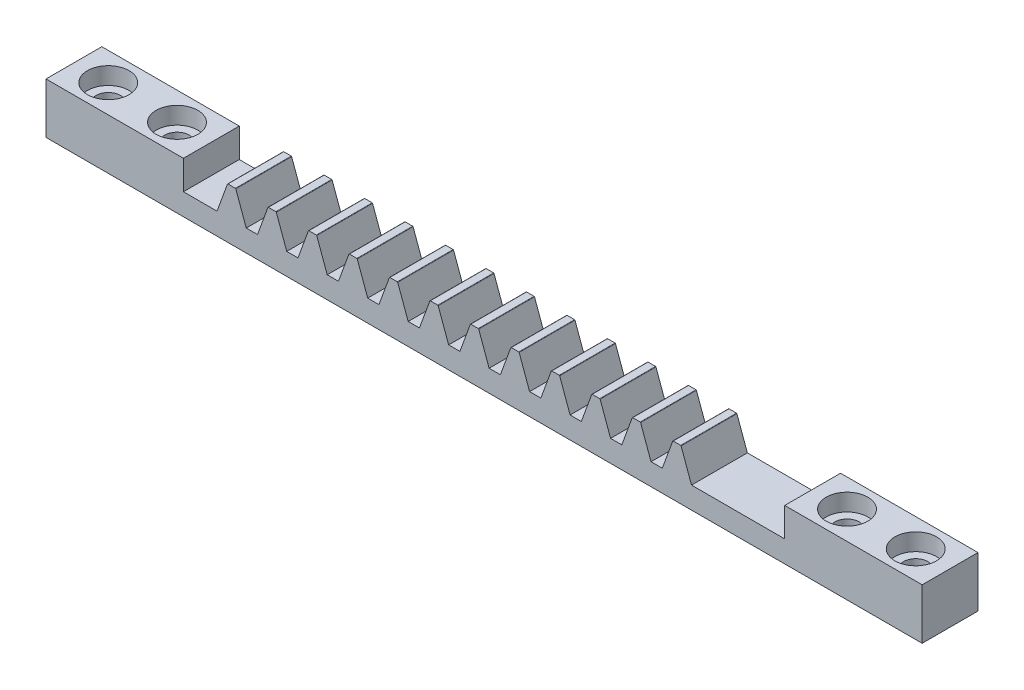
SolidWorks part; units mm, degrees
extrude "Blank" add sketch "BlankSke" against normal blind 6.5
sketch "BlankSke" plane through (0, 0, 0) normal (0, 0, 1) x (1, 0, 0)
  line L1 (0, 0) -> (56.5, 0)
  line L2 (0, 0) -> (0, 6)
  line L3 (0, 6) -> (56.5, 6)
  line L4 (56.5, 0) -> (56.5, 6)
  dimension "Length" = 56.5
  dimension "Blank_height" = 6
ref_plane "Plane1" through (0, 0, 0) normal (0, 0, 1) x (1, 0, 0)
ref_plane "Plane2" through (0, 0, 0) normal (0, 1, 0) x (1, 0, 0)
ref_plane "Plane3" through (0, 0, 0) normal (1, 0, 0) x (0, 0, -1)
sketch "HoldingSke" plane through (0, 0, 0) normal (0, 1, 0) x (1, 0, 0)
  line L0 (0, 0) -> (0.0928, 0.6602)
  line L1 (-15, 0) -> (100, 0) construction
  line L2 (0, 0) -> (-2.1039, 2.3779)
  line L3 (0, 0) -> (-11.863, 4.5341)
  line L4 (0, 0) -> (8.4147, 1.9427)
  line L5 (0, 0) -> (-23.7986, -8.8762)
  line L6 (0, 0) -> (-10.5278, -7.1032)
  line L9 (-71.009, 38.7566) -> (-17.9163, 58.0807)
  line L10 (-76.2, 3.8779) -> (-71.7, 3.8779)
  line L11 (0, 0) -> (-6.5, 0)
  line L12 (-76.2, 101.6) -> (-76.147, 101.6)
  line L13 (24.9733, 27.94) -> (52.9518, 28.4284)
  line L14 (24.9733, 27.94) -> (24.9743, 27.94)
  line L15 (24.9733, 27.94) -> (100.4006, 29.5858)
  circle A0 centre (0, 0) radius 19.05
  circle A1 centre (0, 0) radius 2.25
  circle A2 centre (0, 0) radius 12.7
  dimension "MPH" = 4.5
  dimension "Diameter" = 38.1
  dimension "Num_teeth" = 13
  dimension "Pitch" = 0.6667
  dimension "Show_teeth" = 998
  dimension "Thickness" = 12.7
  dimension "Ap" = 20
  dimension "Pitch_height" = 4.5
  dimension "Width" = 6.5
  dimension "Backlash" = 0.053
  dimension "Addendum_fac" = 1
  dimension "Dedendum_fac" = 1.25
  dimension "Clearance_fac" = 0.25
  dimension "Dedendum_add" = 0.001
  dimension "Length" = 56.5
  dimension "Module" = 1.5
sketch "TooCutSkeIll" plane through (0, 0, 0) normal (0, 0, 1) x (1, 0, 0)
  line L0 (-1.8687, 5.9605) -> (-0.7447, 2.8724)
  line L1 (-0.3914, 2.625) -> (0.3914, 2.625)
  line L2 (0.7447, 2.8724) -> (1.8687, 5.9605)
  line L3 (56.5, 6) -> (0, 6) construction
  line L4 (0, 0) -> (0, 64.897) construction
  line L5 (-13.208, 4.5) -> (12.954, 4.5) construction
  line L6 (0, 0) -> (56.5, 0) construction
  line L7 (1.3371, 4.5) -> (1.3371, 48.7463) construction
  line L8 (-1.3371, 4.5) -> (-1.3371, 48.7463) construction
  line L9 (1.9251, 6) -> (1.9251, 6.0254)
  line L10 (-1.9251, 6) -> (-1.9251, 6.0254)
  line L11 (-1.9251, 6.0254) -> (1.9251, 6.0254)
  arc A0 (0.3914, 2.625) -> (0.7447, 2.8724) centre (0.3914, 3.001) ccw
  arc A1 (-0.7447, 2.8724) -> (-0.3914, 2.625) centre (-0.3914, 3.001) ccw
  arc A2 (1.9251, 6) -> (1.8687, 5.9605) centre (1.9251, 5.94) ccw
  arc A3 (-1.8687, 5.9605) -> (-1.9251, 6) centre (-1.9251, 5.94) ccw
  dimension "Pitch_height" = 4.5
  dimension "Addendum_plus" = 1.5254
  dimension "Pressure_angle" = 20
  dimension "Gap_width" = 2.6742
  dimension "Dedendum" = 1.875
extrude "ToothCutIll" cut sketch "TooCutSkeIll" against normal through all
sketch "TooCutSkeSim" plane through (0, 0, 0) normal (0, 0, 1) x (1, 0, 0)
  line L0 (0.6547, 2.625) -> (-0.6547, 2.625)
  line L1 (1.8923, 6.0254) -> (0.6547, 2.625)
  line L2 (0, 17.4625) -> (0, 53.467) construction
  line L3 (1.8923, 6.0254) -> (-1.8923, 6.0254)
  line L6 (-1.8923, 6.0254) -> (-0.6547, 2.625)
  line L9 (-1.3371, 4.5) -> (1.3371, 4.5) construction
  line L10 (0, 0) -> (56.5, 0) construction
  line L11 (1.3371, 4.5) -> (1.3371, 53.467) construction
  line L12 (-1.3371, 4.5) -> (-1.3371, 53.467) construction
  dimension "Pitch_height" = 4.5
  dimension "Addendum_plus" = 1.5254
  dimension "Pressure_angle" = 20
  dimension "Gap_width" = 2.6742
  dimension "Dedendum" = 1.875
extrude "ToothCutSim" cut sketch "TooCutSkeSim" against normal through all
pattern_linear "TeethCuts" count 13 spacing 4.7124 along (1, 0, 0) of "ToothCutIll", "ToothCutSim"
ref_plane "基准面1" through (0, 0, 0) normal (0, -1, 0) x (-1, 0, 0)
sketch "草图4" plane through (0, 0, 0) normal (0, -1, 0) x (-1, 0, 0)
  line L0 (0, 0) -> (19.255, 0)
  line L1 (19.255, 0) -> (19.255, 6.5)
  line L2 (19.255, 6.5) -> (0, 6.5)
  line L3 (0, 6.5) -> (0, 0)
  line L4 (-56.5, 0) -> (-82.745, 0)
  line L5 (-82.745, 0) -> (-82.745, 6.5)
  line L6 (-82.745, 6.5) -> (-56.5, 6.5)
  line L7 (-56.5, 6.5) -> (-56.5, 0)
  dimension "D1" = 19.255
extrude "凸台-拉伸1" add sketch "草图4" against normal blind 2.625
ref_plane "基准面2" through (0, 2.625, 0) normal (0, 1, 0) x (1, 0, 0)
sketch "草图5" plane through (0, 2.625, 0) normal (0, 1, 0) x (1, 0, 0)
  line L0 (-19.255, 6.5) -> (-3.255, 6.5)
  line L1 (-19.255, 6.5) -> (0.6547, 6.5) construction
  line L2 (-3.255, 6.5) -> (-3.255, 0)
  line L3 (0.6547, 0) -> (-19.255, 0) construction
  line L4 (-3.255, 0) -> (-19.255, 0)
  line L5 (-19.255, 0) -> (-19.255, 6.5)
  line L6 (82.745, 6.5) -> (66.745, 6.5)
  line L7 (55.894, 6.5) -> (82.745, 6.5) construction
  line L8 (66.745, 6.5) -> (66.745, 0)
  line L9 (55.894, 0) -> (82.745, 0) construction
  line L10 (66.745, 0) -> (82.745, 0)
  line L11 (82.745, 0) -> (82.745, 6.5)
  dimension "D1" = 16
extrude "凸台-拉伸2" add sketch "草图5" along normal blind 3.375
ref_plane "基准面3" through (0, 6, 0) normal (0, 1, 0) x (1, 0, 0)
sketch "草图8" plane through (0, 6, 0) normal (0, 1, 0) x (1, 0, 0)
  line L0 (-19.255, 6.5) -> (-11.255, 0)
  line L1 (-19.255, 0) -> (-3.255, 0) construction
  line L2 (-11.255, 0) -> (-3.255, 6.5)
  line L4 (82.745, 6.5) -> (66.745, 6.5) construction
  line L5 (66.745, 6.5) -> (74.745, 6.5)
  line L6 (74.745, 6.5) -> (82.745, 6.5)
  line L7 (74.745, 6.5) -> (74.745, 0)
  line L8 (66.745, 0) -> (82.745, 0) construction
  line L9 (74.745, 0) -> (66.745, 6.5)
  line L11 (74.745, 0) -> (82.745, 6.5)
  circle A0 centre (-15.255, 3.25) radius 1.425
  circle A1 centre (-7.255, 3.25) radius 1.425
  circle A2 centre (78.745, 3.25) radius 1.425
  circle A3 centre (70.745, 3.25) radius 1.425
  dimension "D1" = 8
  dimension "D3" = 2.85
  dimension "D4" = 2.85
  dimension "D5" = 2.85
  dimension "D6" = 2.85
  dimension "D2" = 8
extrude "切除-拉伸1" cut sketch "草图8" against normal through all
chamfer "倒角1" [suppressed] distance 1.35 angle 45
chamfer "倒角2" [suppressed] distance 1.35 angle 45
sketch "草图11" plane through (0, 6, 0) normal (0, 1, 0) x (1, 0, 0)
  circle A0 centre (70.745, 3.25) radius 2.425
  circle A1 centre (78.745, 3.25) radius 2.425
  circle A2 centre (-7.255, 3.25) radius 2.425
  circle A3 centre (-15.255, 3.25) radius 2.425
  circle A4 centre (-15.255, 3.25) radius 1.425
  circle A5 centre (-7.255, 3.25) radius 1.425
  circle A6 centre (70.745, 3.25) radius 1.425
  circle A7 centre (78.745, 3.25) radius 1.425
  dimension "D1" = 2.85
  dimension "D2" = 2.85
  dimension "D3" = 2.85
  dimension "D4" = 2.85
  dimension "D5" = 4.85
  dimension "D6" = 4.85
  dimension "D7" = 4.85
  dimension "D8" = 4.85
extrude "切除-拉伸2" cut sketch "草图11" against normal blind 2
sketch "草图13" plane through (0, 6, 0) normal (0, 1, 0) x (1, 0, 0)
  circle A0 centre (-7.255, 3.25) radius 1.425
  circle A1 centre (-7.255, 3.25) radius 1.675
sketch "草图14" plane through (0, 0, 0) normal (0, -1, 0) x (-1, 0, 0)
  line L1 (19.255, 0) -> (-82.745, 0)
  line L2 (19.255, 0) -> (19.255, 6.5)
  line L3 (19.255, 6.5) -> (-82.745, 6.5)
  line L4 (-82.745, 0) -> (-82.745, 6.5)
  circle A0 centre (15.255, 3.25) radius 1.425
  circle A1 centre (7.255, 3.25) radius 1.425
  circle A2 centre (-70.745, 3.25) radius 1.425
  circle A3 centre (-78.745, 3.25) radius 1.425
extrude "切除-拉伸3" cut sketch "草图14" against normal blind 0.1
equation "' \"Module@HoldingSke\" = 6.35"
equation "' \"Num_teeth@HoldingSke\" = 12"
equation "' \"Ap@HoldingSke\" =  20"
equation "' \"Ap@HoldingSke\" = 20"
equation "' \"Width@HoldingSke\" = 0.25 * 25.4"
equation "' \"Show_teeth@HoldingSke\" = 500"
equation "' \"Backlash@HoldingSke\" = 0.009 * 25.4"
equation "' \"Addendum_fac@HoldingSke\" = 1.0"
equation "' \"Dedendum_fac@HoldingSke\" = 1.25"
equation "' \"Dedendum_add@HoldingSke\" = 0.00005 * 25.4"
equation "' \"Clearance_fac@HoldingSke\" = 0.25"
equation "' \"Pitch_height@HoldingSke\" = 1 * 25.4"
equation "' \"Length@HoldingSke\" = 4.71 * 25.4"
equation "\"Pitch@HoldingSke\" = 1 / \"Module@HoldingSke\""
equation "\"MPH@HoldingSke\" = \"Dedendum_fac@HoldingSke\" / \"Pitch@HoldingSke\" + 2 * \"Dedendum_add@HoldingSke\" + 0.002 * 25.4"
equation "\"MPH@HoldingSke\" = ((sgn( \"MPH@HoldingSke\" - \"Pitch_height@HoldingSke\")+1)*( \"MPH@HoldingSke\" - \"Pitch_height@HoldingSke\"))/2 + \"Pitch_height@HoldingSke\""
equation "\"Blank_height@BlankSke\" = \"Pitch_height@HoldingSke\" + \"Addendum_fac@HoldingSke\"  / \"Pitch@HoldingSke\" "
equation "\"Length@BlankSke\" =  \"Length@HoldingSke\""
equation "\"Face_width@Blank\" = \"Width@HoldingSke\""
equation "\"Pressure_angle@TooCutSkeIll\" = \"Ap@HoldingSke\""
equation "\"Addendum_plus@TooCutSkeIll\" =  \"Addendum_fac@HoldingSke\"  / \"Pitch@HoldingSke\" + 0.001 *25.4"
equation "\"Dedendum@TooCutSkeIll\" = \"Dedendum_fac@HoldingSke\"  / \"Pitch@HoldingSke\""
equation "\"Pitch_height@TooCutSkeIll\" =  \"MPH@HoldingSke\""
equation "\"Gap_width@TooCutSkeIll\" = 3.14159265 / 2 / \"Pitch@HoldingSke\" + 6 * \"Backlash@HoldingSke\""
equation "\"Pressure_angle@TooCutSkeSim\" = \"Ap@HoldingSke\""
equation "\"Addendum_plus@TooCutSkeSim\" =  \"Addendum_fac@HoldingSke\"  / \"Pitch@HoldingSke\" + 0.001 * 25.4"
equation "\"Dedendum@TooCutSkeSim\" = \"Dedendum_fac@HoldingSke\"  / \"Pitch@HoldingSke\""
equation "\"Pitch_height@TooCutSkeSim\" =  \"MPH@HoldingSke\""
equation "\"Gap_width@TooCutSkeSim\" = 3.14159265 / 2 / \"Pitch@HoldingSke\" + 6 * \"Backlash@HoldingSke\""
equation "\"Root_fillet@TooCutSkeIll\" = \"Clearance_fac@HoldingSke\" / \"Pitch@HoldingSke\" + \"Dedendum_add@HoldingSke\""
equation "\"Break_rad@TooCutSkeIll\" = 0.02 / \"Pitch@HoldingSke\" * 2"
equation "\"Linear_pitch@TeethCuts\" = 3.14159265 / \"Pitch@HoldingSke\""
equation "\"Num_teeth@HoldingSke\" = int( ( \"Length@HoldingSke\" + 0 ) / (3.14159265 / \"Pitch@HoldingSke\")) + 0.9999  + 1"
equation " \"Num_teeth@TeethCuts\" = int( \"Show_teeth@HoldingSke\" ) + 1"
equation " \"Num_teeth@TeethCuts\" = ((sgn( \"Num_teeth@TeethCuts\" - \"Num_teeth@HoldingSke\" )-1)*( \"Num_teeth@TeethCuts\" - \"Num_teeth@HoldingSke\" ))/-2+ \"Num_teeth@HoldingSke\""
equation " \"Num_teeth@TeethCuts\" = ((sgn( \"Num_teeth@TeethCuts\" - 2.0)+1)*( \"Num_teeth@TeethCuts\" - 2.0))/2 +2.0"
